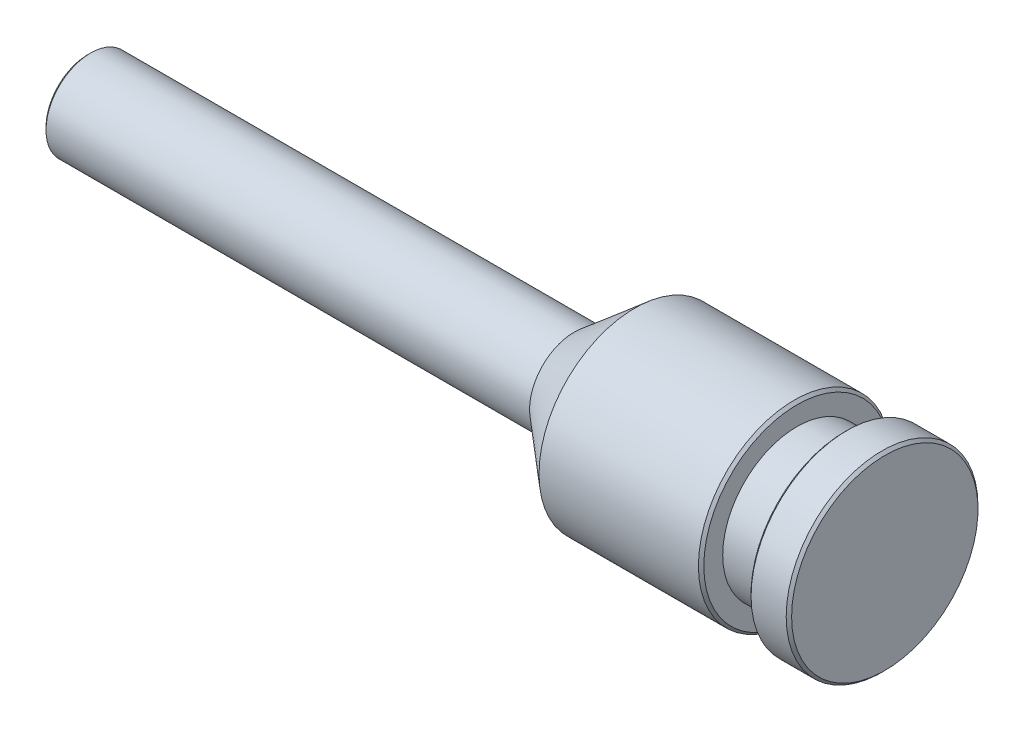
SolidWorks part; units mm, degrees
material "AISI 1020"
ref_plane "Plano superior" through (0, 0, 0) normal (0, 0, 1) x (1, 0, 0)
ref_plane "Plano frontal" through (0, 0, 0) normal (0, 1, 0) x (1, 0, 0)
ref_plane "Plano direito" through (0, 0, 0) normal (1, 0, 0) x (0, 0, -1)
sketch "Esboço1" plane through (0, 0, 0) normal (0, 0, 1) x (1, 0, 0)
  line L0 (13, 0) -> (59, 0)
  line L1 (59, 0) -> (59, 7.1)
  line L2 (59, 7.1) -> (56, 7.1)
  line L3 (56, 7.1) -> (56, 5.5)
  line L4 (56, 5.5) -> (52.5, 5.5)
  line L5 (52.5, 5.5) -> (52.5, 7.1)
  line L6 (52.5, 7.1) -> (40.5, 7.1)
  line L10 (36, 3.3) -> (0, 3.3)
  line L12 (40.5, 7.1) -> (36, 3.3)
  line L14 (0, 1.85) -> (13, 1.85)
  line L15 (13, 1.85) -> (13, 0)
  line L18 (0, 1.85) -> (0, 3.3)
  line L19 (0, 0) -> (74.9665, 0) construction
  dimension "D1" = 23
  dimension "D2" = 13
  dimension "D3" = 1.85
  dimension "D4" = 3
  dimension "D5" = 59
  dimension "D6" = 12
  dimension "D7" = 3.5
  dimension "D8" = 7.1
  dimension "D9" = 3.3
  dimension "D10" = 5.5
revolve "Revolução1" add sketch "Esboço1" angle 360 about L0
cosmetic thread "Representação de rosca1"
chamfer "Chanfro2" distance 0.2 angle 45 4 edges at (0, 0, 3.3) (52.5, 0, 7.1) (56, 0, 7.1) (59, 0, 7.1)
